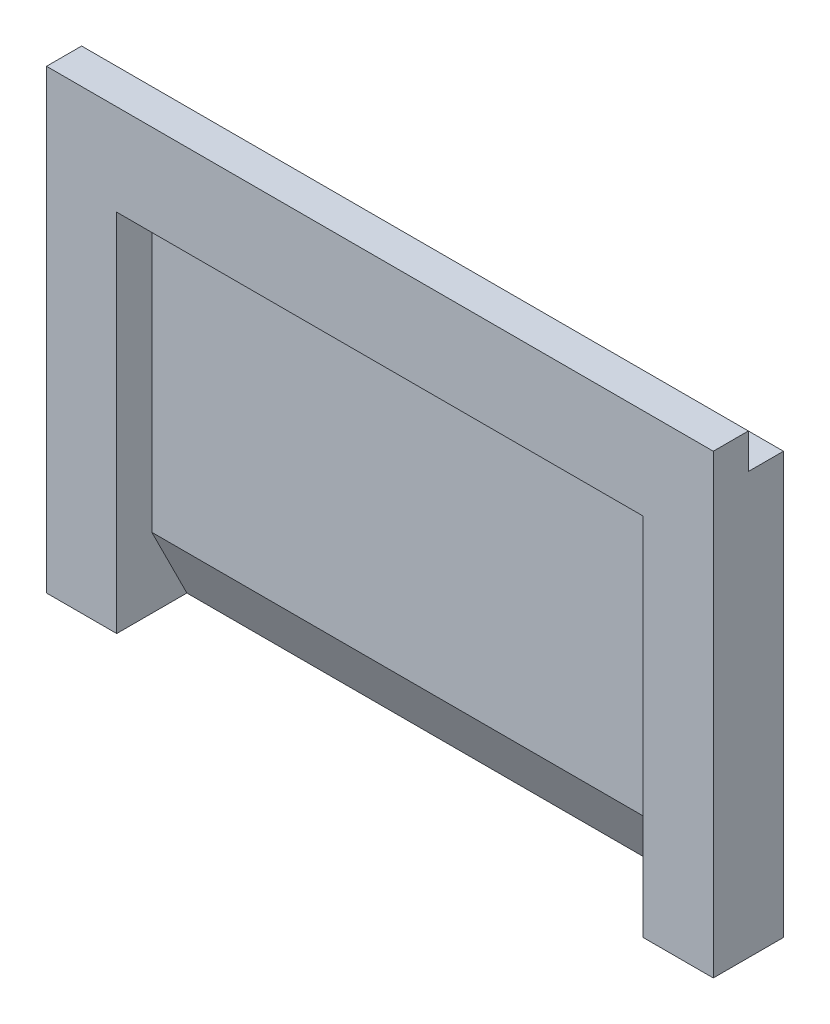
SolidWorks part; units mm, degrees
ref_plane "Front Plane" through (0, 0, 0) normal (0, 0, 1) x (1, 0, 0)
ref_plane "Top Plane" through (0, 0, 0) normal (0, 1, 0) x (1, 0, 0)
ref_plane "Right Plane" through (0, 0, 0) normal (1, 0, 0) x (0, 0, -1)
sketch "Sketch1" plane through (0, 0, 0) normal (0, 0, 1) x (1, 0, 0)
  line L1 (0, 0) -> (95, 0)
  line L2 (0, 0) -> (0, 60)
  line L3 (0, 60) -> (95, 60)
  line L4 (95, 0) -> (95, 60)
  dimension "D1" = 60
  dimension "D2" = 95
extrude "Boss-Extrude1" add sketch "Sketch1" along normal blind 10
sketch "Sketch2" plane through (0, 0, 10) normal (0, 0, 1) x (1, 0, 0)
  line L0 (10, 50) -> (10, 52)
  line L1 (10, 52) -> (85, 52)
  line L2 (85, 52) -> (85, 50)
  line L8 (85, 10) -> (85, 50)
  line L9 (85, 50) -> (10, 50)
  line L10 (10, 50) -> (10, 10)
  line L11 (10, 10) -> (85, 10)
  line L12 (85, 10) -> (85, 50)
  line L14 (10, 50) -> (10, 10)
  line L15 (10, 10) -> (85, 10)
  dimension "D1" = 10
  dimension "D2" = 2
extrude "Cut-Extrude1" cut sketch "Sketch2" against normal blind 5 contours L14 L15 L12 L2 L1 L0
ref_plane "Plane1" through (10, 0, 0) normal (1, 0, 0) x (0, 0, -1)
sketch "Sketch4" plane through (10, 0, 0) normal (1, 0, 0) x (0, 0, -1)
  line L0 (0, 0) -> (-5, 10)
  line L1 (-5, 10) -> (-10, 10)
  line L2 (-10, 10) -> (-10, 0)
  line L3 (-10, 0) -> (0, 0)
extrude "Cut-Extrude2" cut sketch "Sketch4" along normal up to surface (75 mm away) up to face at (85, 31, 7.5)
sketch "Sketch7" plane through (0, 60, 0) normal (0, 1, 0) x (1, 0, 0)
  line L1 (0, -10) -> (95, -10)
  line L2 (0, -10) -> (0, -5)
  line L3 (0, -5) -> (95, -5)
  line L4 (95, -10) -> (95, -5)
  line L5 (95, -10) -> (95, 0) construction
  dimension "D1" = 5
extrude "Boss-Extrude3" add sketch "Sketch7" along normal blind 5
